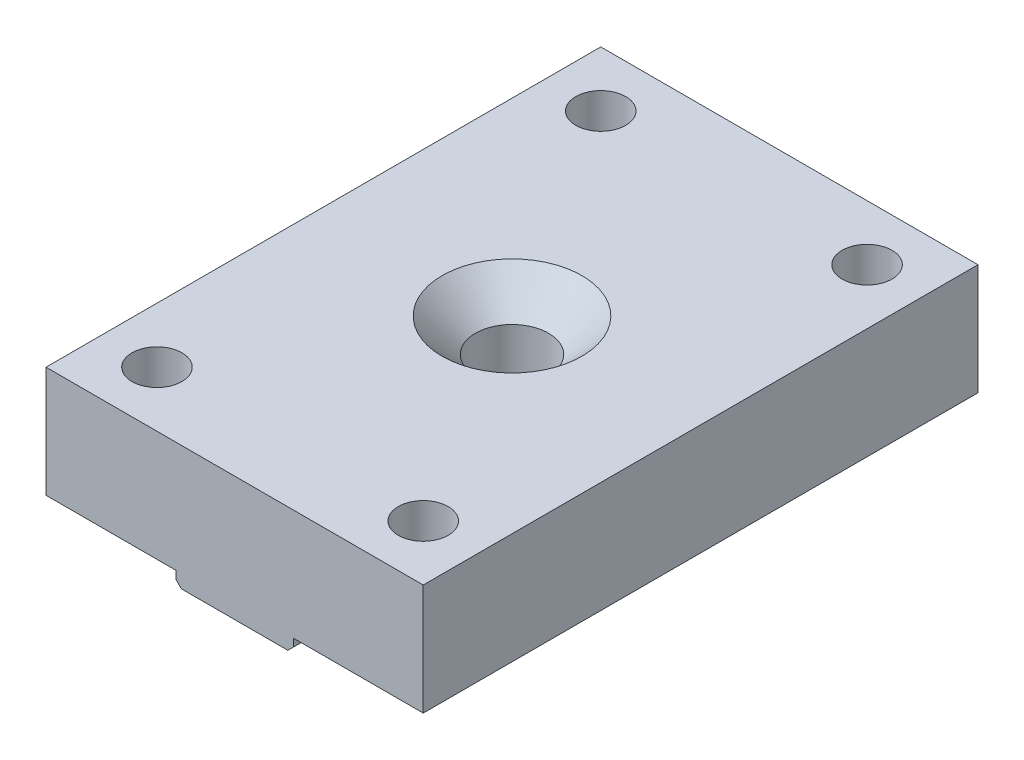
SolidWorks part; units mm, degrees
material "3.1355 (EN-AW 2024)"
ref_plane "Спереди" through (0, 0, 0) normal (0, 0, 1) x (1, 0, 0)
ref_plane "Сверху" through (0, 0, 0) normal (0, 1, 0) x (1, 0, 0)
ref_plane "Справа" through (0, 0, 0) normal (1, 0, 0) x (0, 0, -1)
sketch "Эскиз1" plane through (0, 0, 0) normal (0, 0, 1) x (1, 0, 0)
  line L0 (0, 0) -> (5.3, 0)
  line L1 (5.3, 0) -> (5.3, 1.2)
  line L2 (5.3, 1.2) -> (17, 1.2)
  line L3 (17, 1.2) -> (17, 11.2)
  line L4 (17, 11.2) -> (-17, 11.2)
  line L5 (-17, 11.2) -> (-17, 1.2)
  line L6 (-17, 1.2) -> (-5.3, 1.2)
  line L7 (-5.3, 1.2) -> (-5.3, 0)
  line L8 (-5.3, 0) -> (0, 0)
  dimension "D1" = 10.6
  dimension "D2" = 1.2
  dimension "D3" = 10
  dimension "D4" = 34
extrude "Бобышка-Вытянуть1" add sketch "Эскиз1" against normal blind 50
hole_wizard "Винт M6" positions "Эскиз3" profile "Эскиз5" countersink size "M6" standard "DIN" end condition through all
sketch "Эскиз3" plane through (0, 11.2, 0) normal (0, 1, 0) x (1, 0, 0)
  line L6 (0, 0) -> (0, 25) construction
  line L7 (0, 25) -> (0, 50) construction
  line L8 (17, 50) -> (-17, 50) construction
  point P15 (0, 25)
sketch "Эскиз5" plane through (0, 11.2, -25) normal (1, 0, 0) x (0, 0, 1)
  line L0 (0, 0) -> (0, 11.2)
  line L1 (0, 11.2) -> (3.3, 11.2)
  line L2 (3.3, 11.2) -> (3.3, 3)
  line L3 (3.3, 3) -> (6.3, 0)
  line L5 (6.3, 0) -> (0, 0)
  line L6 (-3.3, 3) -> (-6.3, 0) construction
  line L11 (0, -6.35) -> (0, 107.95) construction
  dimension "Диаметр сквозного отверстия" = 6.6
  dimension "Глубина сквозного отверстия" = 11.2
  dimension "Диаметр передней зенковки" = 12.6
  dimension "Угол передней зенковки" = 90
hole_wizard "Винт M4" positions "Эскиз8" profile "Эскиз7" countersink size "M4" standard "DIN" end condition through all
sketch "Эскиз8" plane through (0, 1.2, 0) normal (0, -1, 0) x (-1, 0, 0)
  line L5 (12, 5) -> (12, 0) construction
  line L6 (17, 0) -> (5.3, 0) construction
  line L13 (-12, 5) -> (-17, 5) construction
  line L14 (-17, 50) -> (-17, 0) construction
  line L19 (12, 45) -> (12, 50) construction
  line L20 (-17, 50) -> (17, 50) construction
  line L22 (12, 5) -> (17, 5) construction
  line L23 (17, 50) -> (17, 0) construction
  point P0 (12, 5)
  point P2 (-12, 5)
  point P40 (12, 45)
  point P42 (-12, 45)
  dimension "D1" = 5
sketch "Эскиз7" plane through (-12, 1.2, -5) normal (1, 0, 0) x (0, 0, -1)
  line L0 (0, 0) -> (0, 10)
  line L1 (0, 10) -> (2.25, 10)
  line L2 (2.25, 10) -> (2.25, 2.45)
  line L3 (2.25, 2.45) -> (4.7, 0)
  line L5 (4.7, 0) -> (0, 0)
  line L6 (-2.25, 2.45) -> (-4.7, 0) construction
  line L11 (0, -6.35) -> (0, 107.95) construction
  dimension "Диаметр сквозного отверстия" = 4.5
  dimension "Глубина сквозного отверстия" = 10
  dimension "Диаметр передней зенковки" = 9.4
  dimension "Угол передней зенковки" = 90
chamfer "Фаска1" distance 0.5 angle 45 2 edges at (-5.3, 0, -25) (5.3, 0, -25)
